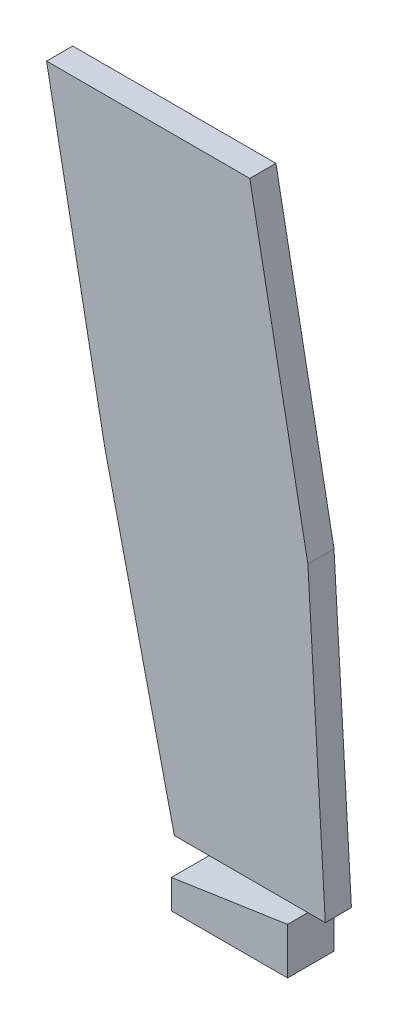
SolidWorks part; units mm, degrees
ref_plane "Front Plane" through (0, 0, 0) normal (0, 0, 1) x (1, 0, 0)
ref_plane "Top Plane" through (0, 0, 0) normal (0, 1, 0) x (1, 0, 0)
ref_plane "Right Plane" through (0, 0, 0) normal (1, 0, 0) x (0, 0, -1)
sketch "Sketch1" plane through (0, 0, 0) normal (0, 0, 1) x (1, 0, 0)
  line L0 (950, 500) -> (950, 550)
  line L1 (950, 550) -> (1150, 580)
  line L2 (1150, 580) -> (1150, 500)
  line L3 (1150, 500) -> (950, 500)
extrude "Boss-Extrude1" add sketch "Sketch1" along normal blind 80
sketch "Sketch2" plane through (0, 0, 0) normal (0, 0, 1) x (1, 0, 0)
  line L0 (920, 580) -> (800, 1100)
  line L1 (800, 1100) -> (700, 1625)
  line L2 (700, 1625) -> (1050, 1625)
  line L3 (1050, 1625) -> (1150, 1100)
  line L4 (1150, 1100) -> (1180, 580)
  line L5 (1180, 580) -> (920, 580)
extrude "Boss-Extrude2" add sketch "Sketch2" along normal blind 45
